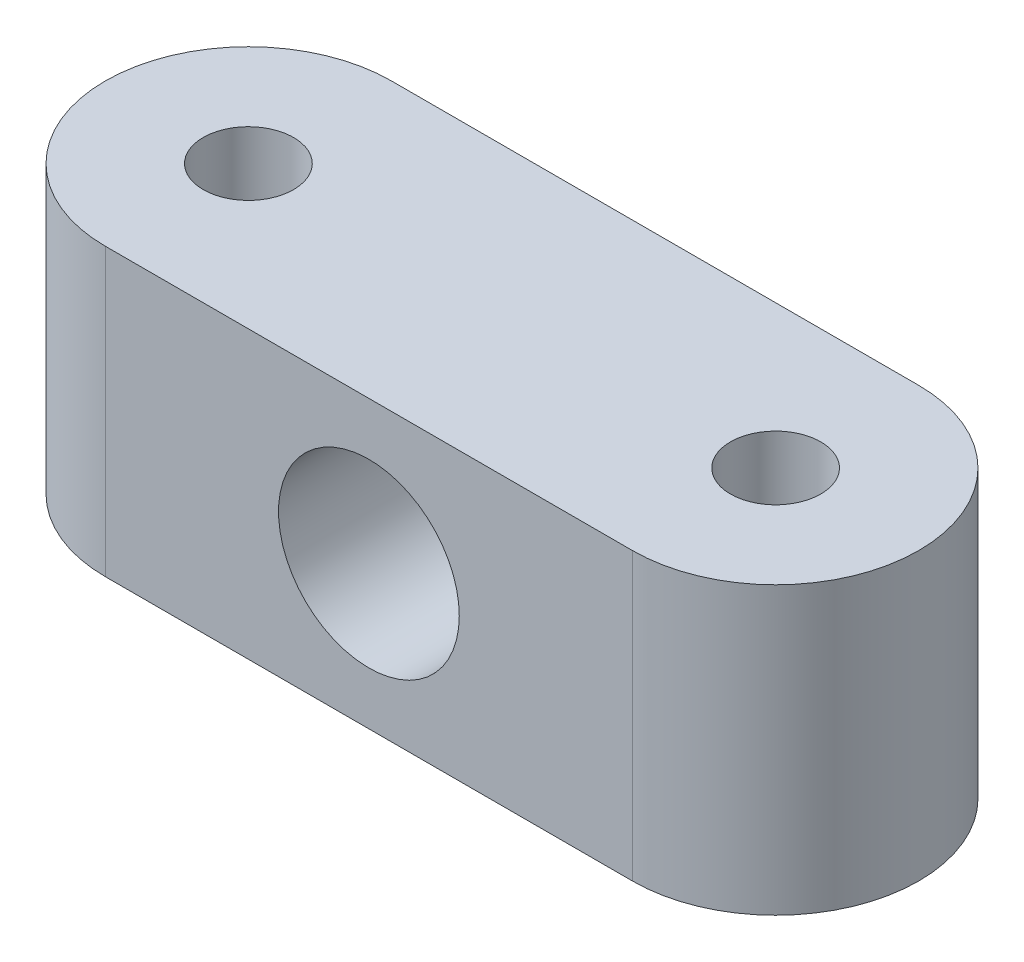
SolidWorks part; units mm, degrees
ref_plane "Front Plane" through (0, 0, 0) normal (0, 0, 1) x (1, 0, 0)
ref_plane "Top Plane" through (0, 0, 0) normal (0, 1, 0) x (1, 0, 0)
ref_plane "Right Plane" through (0, 0, 0) normal (1, 0, 0) x (0, 0, -1)
sketch "Sketch1" plane through (0, 0, 0) normal (0, 1, 0) x (1, 0, 0)
  line L0 (0, 0) -> (70, 0) construction
  line L1 (0, 19) -> (70, 19)
  line L2 (0, -19) -> (70, -19)
  arc A0 (0, 19) -> (0, -19) centre (0, 0) ccw
  arc A1 (70, -19) -> (70, 19) centre (70, 0) ccw
  circle A2 centre (0, 0) radius 6
  circle A3 centre (70, 0) radius 6
  point P3 (35, 0)
  dimension "D2" = 19
  dimension "D3" = 12
  dimension "D1" = 70
extrude "Boss-Extrude1" add sketch "Sketch1" along normal blind 38
sketch "Sketch2" plane through (0, 0, 19) normal (0, 0, 1) x (1, 0, 0)
  line L0 (35, 38) -> (35, 0) construction
  line L3 (0, 38) -> (70, 38) construction
  line L4 (0, 0) -> (70, 0) construction
  circle A0 centre (35, 19) radius 12
  dimension "D1" = 24
extrude "Cut-Extrude1" cut sketch "Sketch2" against normal through all
cosmetic thread "Cosmetic Thread1" parameters "D2"=27
cosmetic thread "Cosmetic Thread2" parameters "D2"=27
